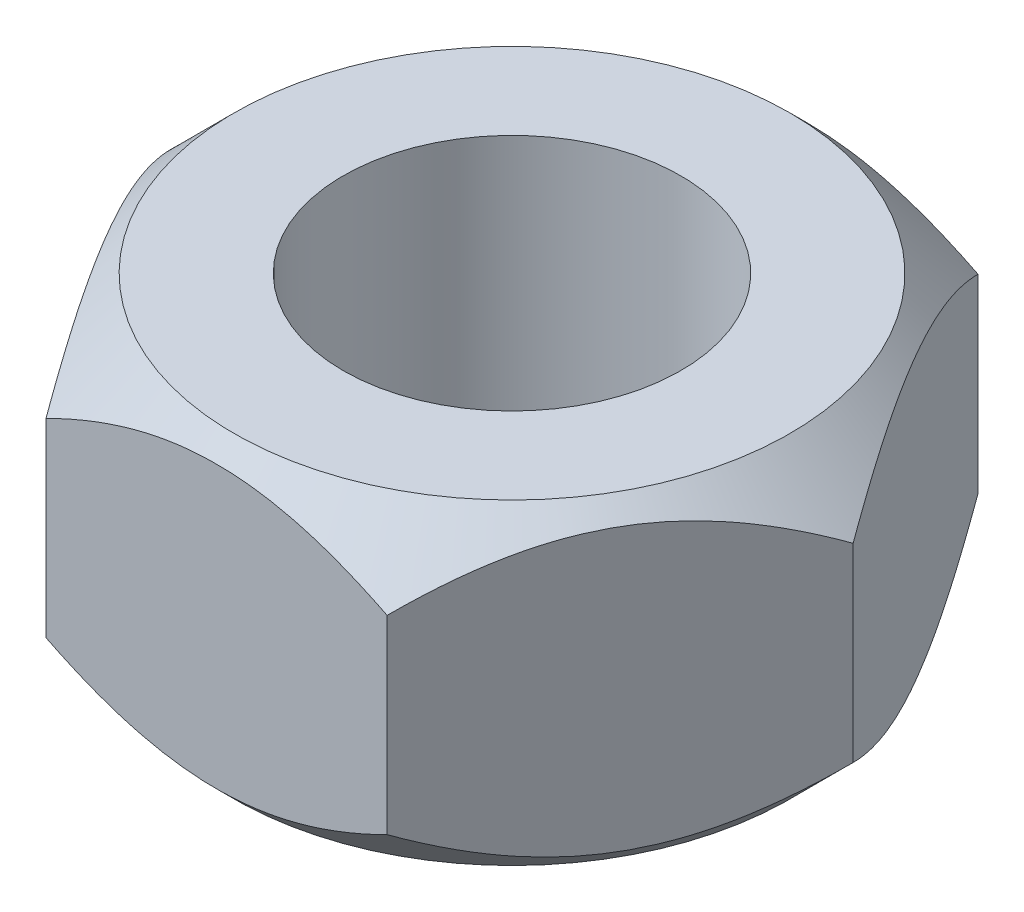
SolidWorks part; units mm, degrees
ref_plane "Front Plane" through (0, 0, 0) normal (0, 0, 1) x (1, 0, 0)
ref_plane "Top Plane" through (0, 0, 0) normal (0, 1, 0) x (1, 0, 0)
ref_plane "Right Plane" through (0, 0, 0) normal (1, 0, 0) x (0, 0, -1)
sketch "Sketch2" plane through (0, 0, 0) normal (0, 1, 0) x (1, 0, 0)
  line L1 (8.0829, 14) -> (-8.0829, 14)
  line L2 (-8.0829, 14) -> (-16.1658, 0)
  line L3 (-16.1658, 0) -> (-8.0829, -14)
  line L4 (-8.0829, -14) -> (8.0829, -14)
  line L5 (8.0829, -14) -> (16.1658, 0)
  line L6 (16.1658, 0) -> (8.0829, 14)
  circle A0 centre (0, 0) radius 14 construction
  dimension "D1" = 28
extrude "Boss-Extrude1" add sketch "Sketch2" along normal mid plane 15
sketch "Sketch3" plane through (0, 0, 0) normal (0, 0, 1) x (1, 0, 0)
  line L5 (13.1658, 7.5) -> (16.1658, 7.5)
  line L6 (16.1658, 7.5) -> (16.1658, 4.5)
  line L7 (16.1658, 4.5) -> (13.1658, 7.5)
  line L8 (0, 0) -> (0, 6.3947) construction
  dimension "D1" = 3
  dimension "D2" = 3
revolve "Cut-Revolve1" cut sketch "Sketch3" angle 360 about L8
mirror "Mirror1" about plane through (0, 0, 0) normal (0, 1, 0) of "Cut-Revolve1"
sketch "Sketch4" plane through (0, 7.5, 0) normal (0, 1, 0) x (1, 0, 0)
  circle A0 centre (0, 0) radius 8
  dimension "D1" = 16
extrude "Cut-Extrude1" cut sketch "Sketch4" against normal through all both and the other way through all
